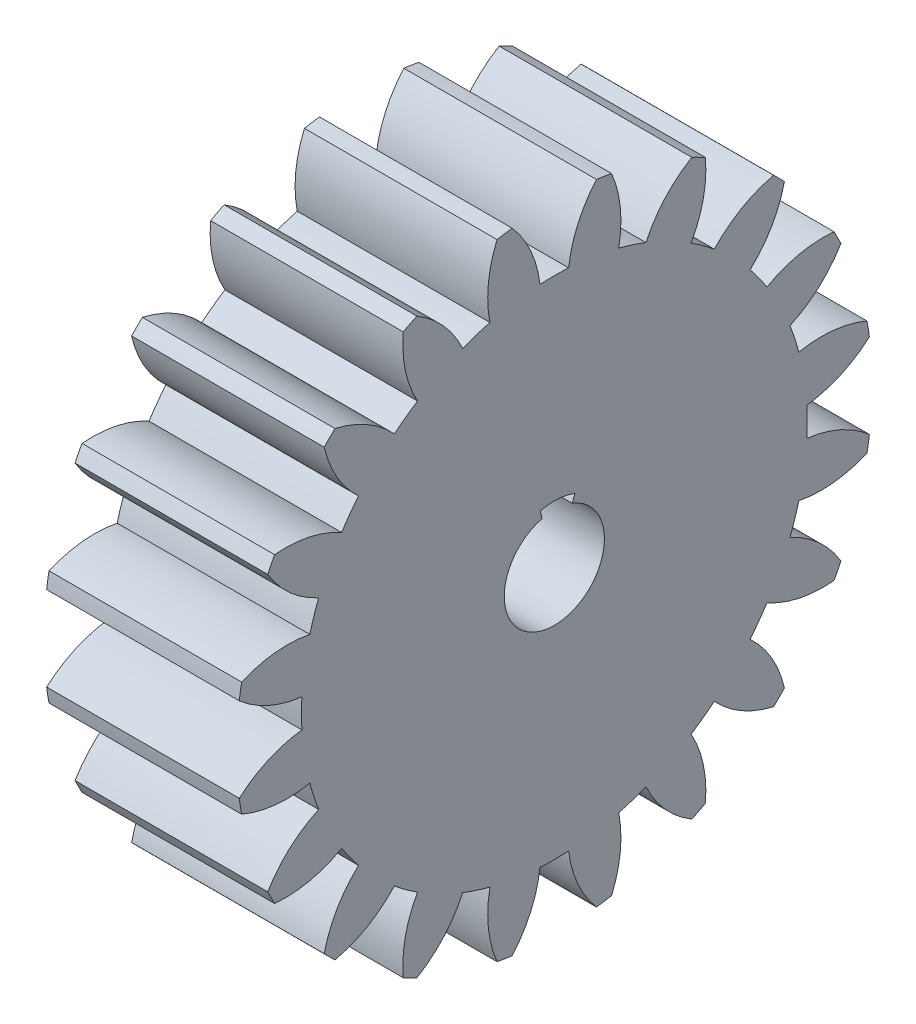
SolidWorks part; units mm, degrees
ref_plane "Plane1" through (0, 0, 0) normal (0, 0, 1) x (1, 0, 0)
ref_plane "Plane2" through (0, 0, 0) normal (0, 1, 0) x (1, 0, 0)
ref_plane "Plane3" through (0, 0, 0) normal (1, 0, 0) x (0, 0, -1)
other "Configuration Table"
sketch "HoldingSke" plane through (0, 0, 0) normal (0, 1, 0) x (1, 0, 0)
  line L0 (0, 0) -> (0.6265, -0.228)
  line L1 (-15, 0) -> (100, 0) construction
  line L2 (0, 0) -> (-2.1039, 2.3779)
  line L3 (0, 0) -> (-11.863, 4.5341)
  line L4 (0, 0) -> (8.1152, 2.9537)
  line L5 (0, 0) -> (-46.8476, -17.4728)
  line L6 (0, 0) -> (-8.2896, -5.593)
  line L7 (-2.1039, 2.3779) -> (8.6586, 51.2059)
  line L8 (-76.2, 54.61) -> (-75.3, 54.61)
  line L9 (-71.009, 38.7566) -> (-53.1078, 45.2721)
  line L10 (-76.2, 71.12) -> (104.1128, 71.12)
  line L11 (0, 0) -> (-10, 0)
  line L12 (-76.2, 101.6) -> (-76.147, 101.6)
  line L13 (24.9733, 27.94) -> (52.9518, 28.4284)
  line L14 (24.9733, 27.94) -> (24.9743, 27.94)
  line L15 (24.9733, 27.94) -> (100.4006, 29.5858)
  line L16 (-63.627, -1.5) -> (-12.827, -1.5)
  circle A0 centre (0, 0) radius 2.5
  circle A1 centre (0, 0) radius 13.124
  circle A2 centre (0, 0) radius 37.5
  circle A3 centre (0, 0) radius 2.5
  dimension "MHD" = 26.248
  dimension "Hub_dia" = 75
  dimension "Bore" = 5
  dimension "MBD" = 5
  dimension "Num_teeth" = 20
  dimension "Pitch" = 0.6667
  dimension "Overall_len" = 50
  dimension "Show_teeth" = 20
  dimension "Thickness" = 10
  dimension "OAL" = 50.0001
  dimension "T_dim" = 0.9
  dimension "Ap" = 20
  dimension "H" = 19.05
  dimension "Pitch_radius" = 180.3128
  dimension "Width" = 10
  dimension "Backlash" = 0.053
  dimension "Addendum_fac" = 1
  dimension "Dedendum_fac" = 1.25
  dimension "Clearance_fac" = 0.25
  dimension "Dedendum_add" = 0.001
  dimension "Module" = 1.5
sketch "BasProSke" plane through (0, 0, 0) normal (0, 1, 0) x (1, 0, 0)
  line L0 (-10, 0) -> (60, 0) construction
  line L1 (0, 0) -> (0, 16.5)
  line L2 (0, 0) -> (10, 0)
  line L3 (10, 0) -> (10, 16.5)
  line L4 (10, 16.5) -> (0, 16.5)
  dimension "Thickness" = 10
  dimension "Diameter" = 33
revolve "Base-Revolve" add sketch "BasProSke" angle 360 about L0
sketch "TooCutSke" plane through (0, 0, 0) normal (1, 0, 0) x (0, 0, -1)
  line L1 (0, 0) -> (0, 107) construction
  line L2 (0, 0) -> (-1.2696, 14.9462) construction
  line L3 (0, 0) -> (-4.6808, 29.5532) construction
  line L4 (-1.2696, 14.9462) -> (-2.3404, 14.7766) construction
  arc A0 (0.7438, 13.1029) -> (-0.7438, 13.1029) centre (0, 0) ccw
  arc A1 (2.21, 16.377) -> (-2.21, 16.377) centre (0, 0) ccw
  circle A2 centre (0, 0) radius 15 construction
  circle A3 centre (0, 0) radius 14.0954 construction
  arc A4 (-0.7438, 13.1029) -> (-2.21, 16.377) centre (-6.7025, 12.3999) ccw
  arc A5 (2.21, 16.377) -> (0.7438, 13.1029) centre (6.7025, 12.3999) ccw
  dimension "Root_dia" = 26.248
  dimension "Overcut_dia" = 33.0508
  dimension "Pitch_dia" = 30
  dimension "Base_dia" = 28.1908
  dimension "Flank_rad" = 6
  dimension "Half_ang" = 9
  dimension "Half_CT" = 1.0841
extrude "ToothCut" cut sketch "TooCutSke" along normal through all
fillet "Breaks" [suppressed] radius 0.03
fillet "RootFillets" [suppressed] radius 0.376
pattern_circular "TeethCuts" count 20 every 18 about axis through (-10, 0, 0) along (1, 0, 0) of "ToothCut", "RootFillets", "Breaks"
sketch "HubNeaOneSke" plane through (0, 0, 0) normal (-1, 0, 0) x (0, 0, 1)
  circle A0 centre (0, 0) radius 13.124
  dimension "Diameter" = 26.248
extrude "HubNearOne" [suppressed] add sketch "HubNeaOneSke" along normal blind 40.0001
sketch "HubNeaBotSke" plane through (0, 0, 0) normal (-1, 0, 0) x (0, 0, 1)
  circle A0 centre (0, 0) radius 13.124
  dimension "Diameter" = 26.248
extrude "HubNearBoth" [suppressed] add sketch "HubNeaBotSke" along normal blind 20
ref_plane "FarPln" through (10, 0, 0) normal (1, 0, 0) x (0, 0, -1)
sketch "HubFarSke" plane through (10, 0, 0) normal (1, 0, 0) x (0, 0, -1)
  circle A0 centre (0, 0) radius 13.124
  dimension "Diameter" = 26.248
extrude "HubFar" [suppressed] add sketch "HubFarSke" along normal blind 20
sketch "BorSke" plane through (0, 0, 0) normal (1, 0, 0) x (0, 0, -1)
  circle A0 centre (0, 0) radius 2.5
  dimension "Diameter" = 5
extrude "Bore" cut sketch "BorSke" along normal mid plane 100.0001
sketch "KeySke" plane through (0, 0, 0) normal (1, 0, 0) x (0, 0, -1)
  line L0 (-1, 0) -> (-1, 3.4)
  line L1 (-1, 3.4) -> (1, 3.4)
  line L2 (1, 3.4) -> (1, 0)
  line L3 (0, 0) -> (0, 34) construction
  line L4 (-1, 0) -> (1, 0)
  dimension "Offset" = 3.4
  dimension "Width" = 2
extrude "Keyway" [suppressed] cut sketch "KeySke" along normal mid plane 100.0001
pattern_circular "Keyway2" [suppressed] count 2 every 90 about axis through (-10, 0, 0) along (1, 0, 0)
sketch "Sketch1" plane through (0, 0, 0) normal (-1, 0, 0) x (0, 0, 1)
  line L5 (-1.0713, 2.8022) -> (-0.9284, 2.4286)
  line L6 (0.6324, 2.5219) -> (0.7297, 2.9099)
  arc A0 (-0.9284, 2.4286) -> (0.8817, 2.4459) centre (0, 0) ccw
  arc A2 (-1.0713, 2.8022) -> (0.7297, 2.9099) centre (0, 0) cw
  arc A4 (0.8817, 2.4459) -> (0.6324, 2.5219) centre (0, 0) ccw
extrude "Cut-Extrude1" cut sketch "Sketch1" against normal through all
equation "' \"Module@HoldingSke\" = 6.35"
equation "' \"Num_teeth@HoldingSke\" = 12"
equation "' \"Ap@HoldingSke\" =  20"
equation "' \"Ap@HoldingSke\" = 20"
equation "' \"Width@HoldingSke\" = 0.5 * 25.4"
equation "' \"Hub_dia@HoldingSke\"= 1 * 25.4"
equation "' \"Hub_dia@HoldingSke\" = 1 * 25.4"
equation "' \"Overall_len@HoldingSke\" = 1.0 * 25.4"
equation "' \"Bore@HoldingSke\" = 0.75 * 25.4"
equation "' \"T_dim@HoldingSke\" = 0.1 * 25.4"
equation "' \"Width@KeySke\" = 0.25 * 25.4"
equation "' \"Show_teeth@HoldingSke\" = 13"
equation "' \"Backlash@HoldingSke\" = 0.009 * 25.4"
equation "' \"Addendum_fac@HoldingSke\" = 1.0"
equation "' \"Dedendum_fac@HoldingSke\" = 1.25"
equation "' \"Dedendum_add@HoldingSke\" = 0.00005 * 25.4"
equation "' \"Clearance_fac@HoldingSke\" = 0.25"
equation "\"Pitch@HoldingSke\" = 1 / \"Module@HoldingSke\""
equation "\"Overcut_dia@TooCutSke\" = (\"Num_teeth@HoldingSke\" + 2 * \"Addendum_fac@HoldingSke\") / \"Pitch@HoldingSke\" + 0.002 * 25.4"
equation "\"Pitch_dia@TooCutSke\" = \"Num_teeth@HoldingSke\" / \"Pitch@HoldingSke\""
equation "\"Base_dia@TooCutSke\" = \"Num_teeth@HoldingSke\" / \"Pitch@HoldingSke\" * cos((\"Ap@HoldingSke\"  * 3.14159265 / 180))"
equation "\"Root_dia@TooCutSke\" = (\"Num_teeth@HoldingSke\" + 2) / \"Pitch@HoldingSke\" - 2 * (\"Addendum_fac@HoldingSke\" + \"Dedendum_fac@HoldingSke\") / \"Pitch@HoldingSke\" - \"Dedendum_add@HoldingSke\" * 2"
equation "\"Half_ang@TooCutSke\" = 180 / \"Num_teeth@HoldingSke\""
equation "\"Half_CT@TooCutSke\" = \"Num_teeth@HoldingSke\" / \"Pitch@HoldingSke\" * sin((3.14159265 / 2 / \"Num_teeth@HoldingSke\")) / 2 - 7 * \"Backlash@HoldingSke\" / 4"
equation "\"Flank_rad@TooCutSke\" = \"Num_teeth@HoldingSke\" / \"Pitch@HoldingSke\" / 5"
equation "\"Radius@RootFillets\" = \"Clearance_fac@HoldingSke\" / \"Pitch@HoldingSke\" + \"Dedendum_add@HoldingSke\""
equation "\"Break_rad@Breaks\" = 0.02 / \"Pitch@HoldingSke\""
equation "\"Thickness@HoldingSke\" = \"Width@HoldingSke\""
equation "\"OAL@HoldingSke\" = \"Thickness@HoldingSke\""
equation "\"MHD@HoldingSke\" = (\"Num_teeth@HoldingSke\" + 2) / \"Pitch@HoldingSke\" - 2 * (\"Addendum_fac@HoldingSke\" + \"Dedendum_fac@HoldingSke\")  / \"Pitch@HoldingSke\" - \"Dedendum_add@HoldingSke\" * 2"
equation "\"MBD@HoldingSke\" = (\"Num_teeth@HoldingSke\" + 2) / \"Pitch@HoldingSke\" - 2 * (\"Addendum_fac@HoldingSke\" + \"Dedendum_fac@HoldingSke\")  / \"Pitch@HoldingSke\" - \"Dedendum_add@HoldingSke\" * 2 - 0.002 * 25.4"
equation "\"MHD@HoldingSke\" = ((sgn( \"MHD@HoldingSke\" - \"Hub_dia@HoldingSke\" )-1)*( \"MHD@HoldingSke\" - \"Hub_dia@HoldingSke\" ))/-2+ \"Hub_dia@HoldingSke\""
equation "\"MBD@HoldingSke\" = ((sgn( \"MBD@HoldingSke\" - \"Bore@HoldingSke\" )-1)*( \"MBD@HoldingSke\" - \"Bore@HoldingSke\" ))/-2+ \"Bore@HoldingSke\""
equation "\"OAL@HoldingSke\" = ((sgn( \"OAL@HoldingSke\" - \"Overall_len@HoldingSke\" )+1)*( \"OAL@HoldingSke\" - \"Overall_len@HoldingSke\" ))/2 + \"Overall_len@HoldingSke\" + 0.000002 * 25.4"
equation "\"Num_teeth@TeethCuts\" = int( \"Show_teeth@HoldingSke\" ) + 1"
equation "\"Num_teeth@TeethCuts\" = ((sgn( \"Num_teeth@TeethCuts\" - \"Num_teeth@HoldingSke\" )-1)*( \"Num_teeth@TeethCuts\" - \"Num_teeth@HoldingSke\" ))/-2+ \"Num_teeth@HoldingSke\""
equation "\"Num_teeth@TeethCuts\" = ((sgn( \"Num_teeth@TeethCuts\" - 2.0)+1)*( \"Num_teeth@TeethCuts\" - 2.0))/2 +2.0"
equation "\"Angle@TeethCuts\" = 360.0 / \"Num_teeth@HoldingSke\""
equation "\"Diameter@BasProSke\" = (\"Num_teeth@HoldingSke\" + 2 * \"Addendum_fac@HoldingSke\") / \"Pitch@HoldingSke\""
equation "\"Thickness@BasProSke\"  = \"Thickness@HoldingSke\""
equation "' \"Fillet_rad@BasProSke\" =  \"Thickness@HoldingSke\" * 0.05"
equation "' \"Fillet_rad@BasProSke\" = \"Thickness@HoldingSke\" * 0.05"
equation "\"MHD@HoldingSke\" = ((sgn( \"MHD@HoldingSke\" - \"Root_dia@TooCutSke\" )-1)*( \"MHD@HoldingSke\" - \"Root_dia@TooCutSke\" ))/-2+ \"Root_dia@TooCutSke\""
equation "\"Diameter@HubNeaOneSke\" = \"MHD@HoldingSke\""
equation "\"Length@HubNearOne\" = \"OAL@HoldingSke\" - \"Thickness@BasProSke\""
equation "\"Diameter@HubNeaBotSke\" = \"MHD@HoldingSke\""
equation "\"Length@HubNearBoth\" = ( \"OAL@HoldingSke\" - \"Thickness@BasProSke\" ) / 2.0"
equation "\"Thickness@FarPln\" = \"Thickness@BasProSke\""
equation "\"Diameter@HubFarSke\" = \"MHD@HoldingSke\""
equation "\"Length@HubFar\" = ( \"OAL@HoldingSke\" - \"Thickness@BasProSke\" ) / 2.0"
equation "\"Diameter@BorSke\" = \"MBD@HoldingSke\""
equation "\"D1@Bore\" = \"OAL@HoldingSke\" * 2.0"
equation "\"D1@Keyway\" = \"OAL@HoldingSke\" * 2.0"
equation "\"Offset@KeySke\" = \"T_dim@HoldingSke\" + \"MBD@HoldingSke\" / 2.0"
